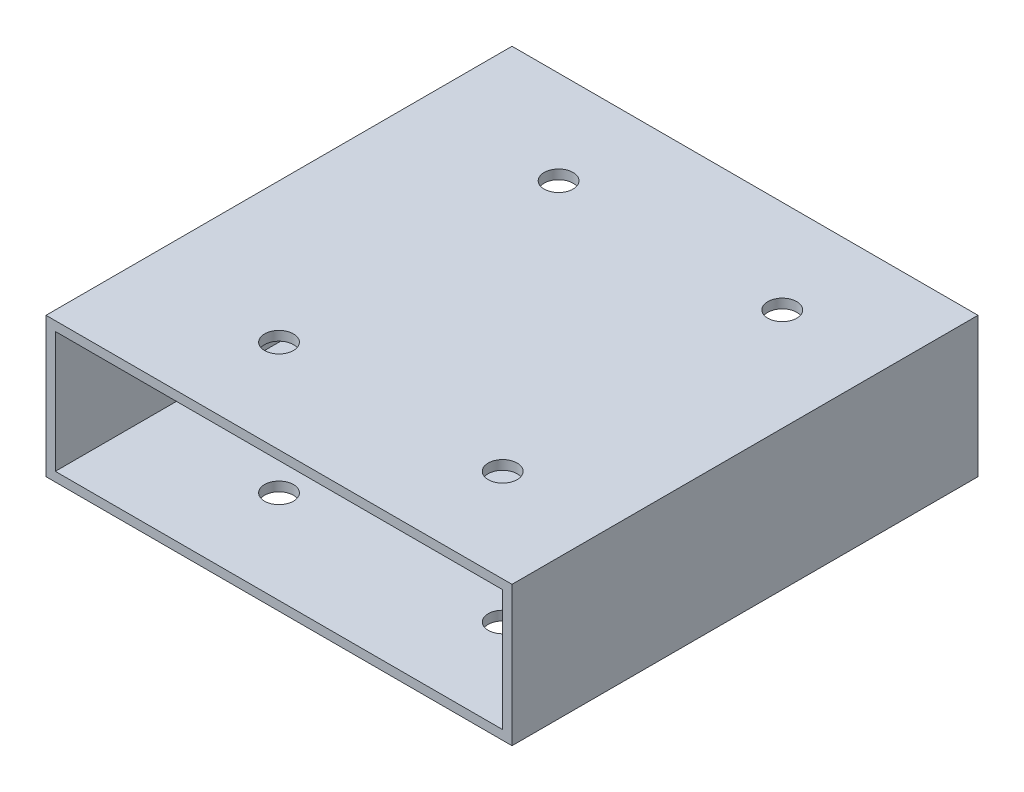
SolidWorks part; units mm, degrees
ref_plane "前视基准面" through (0, 0, 0) normal (0, 0, 1) x (1, 0, 0)
ref_plane "上视基准面" through (0, 0, 0) normal (0, 1, 0) x (1, 0, 0)
ref_plane "右视基准面" through (0, 0, 0) normal (1, 0, 0) x (0, 0, -1)
other "Configuration Table"
sketch "草图1" plane through (0, 0, 0) normal (0, 0, 1) x (1, 0, 0)
  line L1 (0, 0) -> (50, 0)
  line L2 (0, 0) -> (0, 15)
  line L3 (0, 15) -> (50, 15)
  line L4 (50, 0) -> (50, 15)
  line L5 (1, 1) -> (49, 1)
  line L6 (1, 1) -> (1, 14)
  line L7 (1, 14) -> (49, 14)
  line L8 (49, 1) -> (49, 14)
  dimension "D1" = 50
  dimension "D2" = 15
  dimension "D3" = 1
  dimension "D4" = 1
  dimension "D5" = 1
  dimension "D6" = 1
extrude "凸台-拉伸1" add sketch "草图1" along normal blind 50
sketch "草图2" plane through (0, 15, 0) normal (0, 1, 0) x (1, 0, 0)
  circle A1 centre (39, -10) radius 1.55
  circle A2 centre (39, -10) radius 1.55
  circle A3 centre (15, -10) radius 1.55
  circle A4 centre (15, -10) radius 1.55
  circle A5 centre (15, -40) radius 1.55
  circle A6 centre (15, -40) radius 1.55
  circle A7 centre (39, -40) radius 1.55
  circle A8 centre (39, -40) radius 1.55
  dimension "D1" = 0
  dimension "D2" = 0
  dimension "D3" = 0
  dimension "D4" = 0
extrude "切除-拉伸1" cut sketch "草图2" against normal through all
